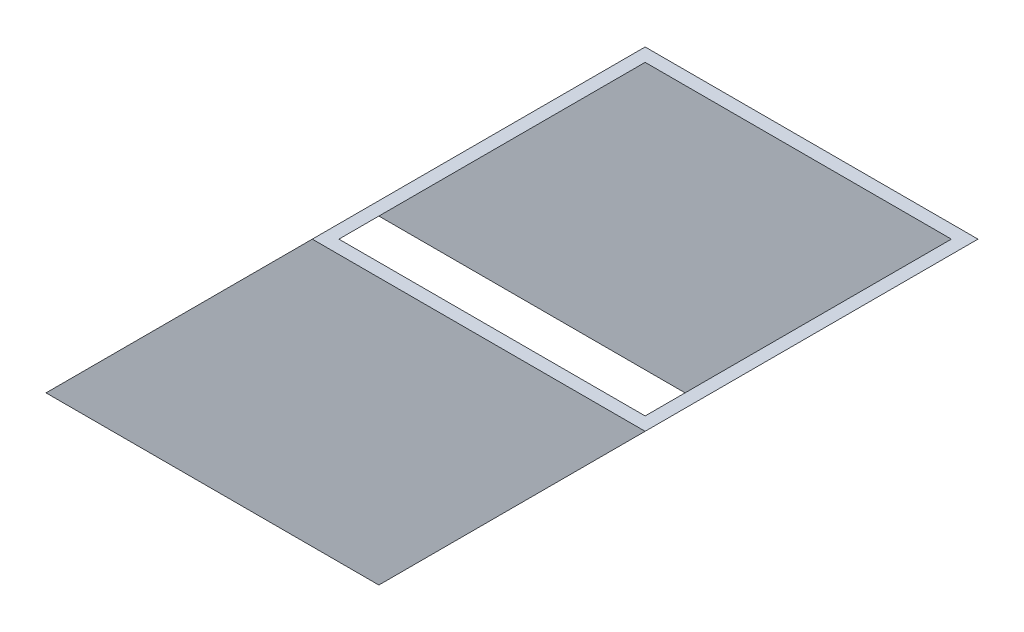
SolidWorks part; units mm, degrees
material "ABS"
ref_plane "Alzado" through (0, 0, 0) normal (0, 0, 1) x (1, 0, 0)
ref_plane "Planta" through (0, 0, 0) normal (0, 1, 0) x (1, 0, 0)
ref_plane "Vista lateral" through (0, 0, 0) normal (1, 0, 0) x (0, 0, -1)
sketch "Croquis2" plane through (0, 0, 0) normal (0, 0, 1) x (1, 0, 0)
  line L0 (-42.342, -30.3532) -> (7.658, -30.3532)
  line L1 (7.658, -30.3532) -> (-32.342, -70.3532)
  line L2 (-32.342, -70.3532) -> (-82.342, -70.3532)
  line L3 (-82.342, -70.3532) -> (-42.342, -30.3532)
  dimension "D1" = 50
  dimension "D2" = 50
  dimension "D3" = 40
  dimension "D4" = 45
extrude "Saliente-Extruir1" add sketch "Croquis2" along normal blind 2
sketch "Croquis3" plane through (0, 0, 0) normal (0, 0, -1) x (-1, 0, 0)
  line L0 (-5.658, -30.3532) -> (-7.658, -30.3532)
  line L1 (-7.658, -30.3532) -> (42.342, -30.3532) construction
  line L5 (42.342, -30.3532) -> (40.342, -30.3532)
  line L13 (-7.658, -30.3532) -> (32.342, -70.3532)
  line L14 (32.342, -70.3532) -> (34.342, -70.3532)
  line L15 (82.342, -70.3532) -> (32.342, -70.3532) construction
  line L16 (34.342, -70.3532) -> (-5.658, -30.3532)
  line L17 (40.342, -30.3532) -> (80.342, -70.3532)
  line L18 (80.342, -70.3532) -> (82.342, -70.3532)
  line L19 (82.342, -70.3532) -> (42.342, -30.3532)
  dimension "D1" = 2
  dimension "D2" = 2
  dimension "D3" = 2
  dimension "D4" = 2
extrude "Saliente-Extruir2" add sketch "Croquis3" along normal blind 46
sketch "Croquis4" plane through (0, 0, -46) normal (0, 0, -1) x (-1, 0, 0)
  line L0 (-7.658, -30.3532) -> (42.342, -30.3532)
  line L1 (42.342, -30.3532) -> (82.342, -70.3532)
  line L2 (82.342, -70.3532) -> (32.342, -70.3532)
  line L3 (32.342, -70.3532) -> (-7.658, -30.3532)
extrude "Saliente-Extruir3" add sketch "Croquis4" along normal blind 2
sketch "Croquis5" plane through (-5.9944, 5.9944, 0) normal (-0.7071, 0.7071, 0) x (0, 0, 1)
  line L0 (-23, -107.9718) -> (-23, -77.9718) construction
  line L1 (2, -107.9718) -> (-48, -107.9718) construction
  line L2 (-23.25, -77.9718) -> (-22.75, -77.9718) construction
  line L3 (-22.75, -77.9718) -> (-21.25, -77.9718) construction
  line L4 (-23.25, -77.9718) -> (-24.75, -77.9718) construction
  circle A1 centre (-24.75, -77.9718) radius 1.5
  circle A2 centre (-21.25, -77.9718) radius 1.5
  point P7 (-23, -77.9718)
  dimension "D1" = 0.5
  dimension "D2" = 30
  dimension "D3" = 1.5
  dimension "D4" = 1.5
extrude "Cortar-Extruir1" cut sketch "Croquis5" against normal up to surface (1.4142 mm away) up to face at (-60.342, -50.3532, -23)
sketch "Croquis8" plane through (-5.9944, 5.9944, 0) normal (-0.7071, 0.7071, 0) x (0, 0, 1)
  line L0 (-23, -107.9718) -> (-23, -77.9718) construction
  line L1 (2, -107.9718) -> (-48, -107.9718) construction
  line L2 (-28, -77.9718) -> (-18, -77.9718) construction
  line L3 (-28, -80.7218) -> (-28, -75.2218)
  line L4 (-28, -75.2218) -> (-18, -75.2218)
  line L5 (-18, -75.2218) -> (-18, -80.7218)
  line L6 (-18, -80.7218) -> (-28, -80.7218)
  point P7 (-23, -77.9718)
  point P10 (-28, -77.9718)
  dimension "D1" = 10
  dimension "D2" = 30
  dimension "D3" = 5.5
extrude "Cortar-Extruir2" cut sketch "Croquis8" against normal blind 1 draft 45
